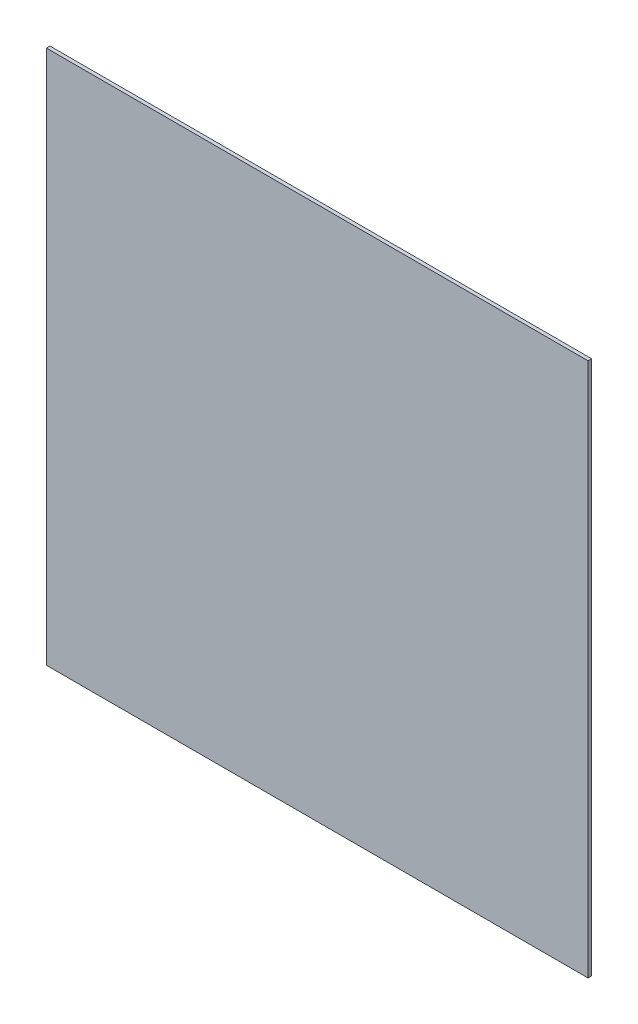
SolidWorks part; units mm, degrees
ref_plane "Спереди" through (0, 0, 0) normal (0, 0, 1) x (1, 0, 0)
ref_plane "Сверху" through (0, 0, 0) normal (0, 1, 0) x (1, 0, 0)
ref_plane "Справа" through (0, 0, 0) normal (1, 0, 0) x (0, 0, -1)
sketch "Эскиз1" plane through (0, 0, 0) normal (0, 0, 1) x (1, 0, 0)
  line L1 (0, 0) -> (1520, 0)
  line L2 (0, 0) -> (0, 1500)
  line L3 (0, 1500) -> (1520, 1500)
  line L4 (1520, 0) -> (1520, 1500)
  dimension "D1" = 1500
  dimension "D2" = 1520
extrude "Бобышка-Вытянуть1" add sketch "Эскиз1" along normal blind 10
